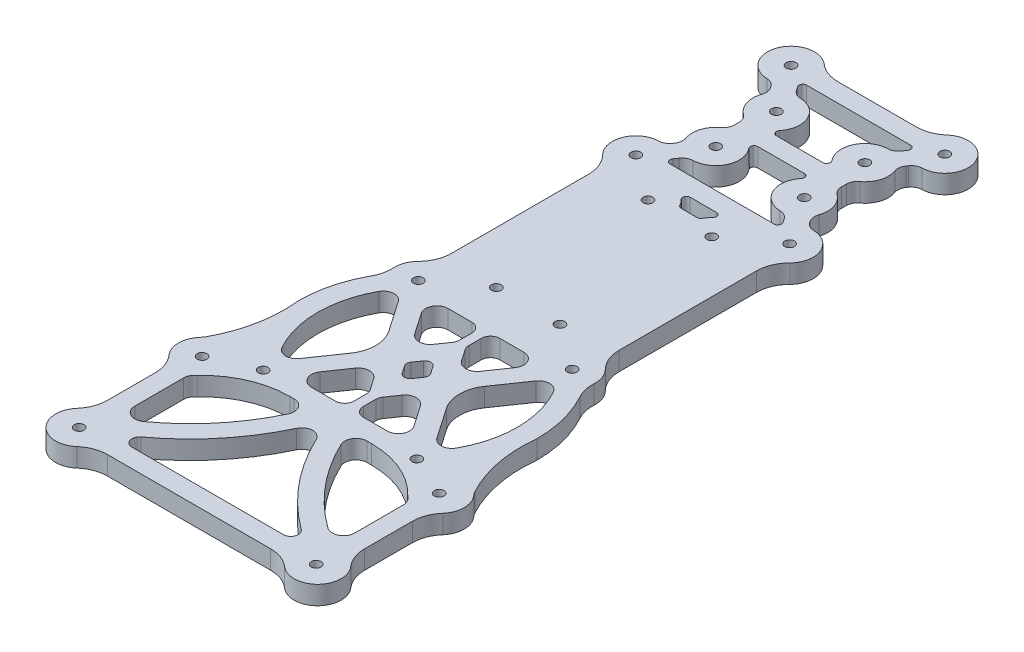
SolidWorks part; units mm, degrees
material "Acrylic (Medium-high impact)"
ref_plane "Front Plane" through (0, 0, 0) normal (0, 0, 1) x (1, 0, 0)
ref_plane "Top Plane" through (0, 0, 0) normal (0, 1, 0) x (1, 0, 0)
ref_plane "Right Plane" through (0, 0, 0) normal (1, 0, 0) x (0, 0, -1)
sketch "Sketch1" plane through (0, 0, 0) normal (0, 1, 0) x (1, 0, 0)
  line L0 (-37.2814, 102.0445) -> (37.2814, 102.0445) construction
  line L1 (-16.2987, -57.0117) -> (-23.4407, -46.6537)
  line L2 (-28.575, -23.3842) -> (-28.575, 23.3842)
  line L3 (-28.575, 39.1353) -> (28.575, 39.1353) construction
  line L4 (28.575, -23.3842) -> (28.575, 23.3842)
  line L5 (-28.575, -39.1353) -> (28.575, 39.1353) construction
  line L6 (-28.575, 39.1353) -> (28.575, -39.1353) construction
  line L7 (-10.8458, -25.8445) -> (10.8458, -25.8445) construction
  line L8 (-10.8458, -25.8445) -> (-10.8458, 25.8445) construction
  line L9 (-10.8458, 25.8445) -> (10.8458, 25.8445) construction
  line L10 (10.8458, -25.8445) -> (10.8458, 25.8445) construction
  line L11 (-10.8458, -25.8445) -> (10.8458, 25.8445) construction
  line L12 (-10.8458, 25.8445) -> (10.8458, -25.8445) construction
  line L13 (-87.957, -127.4445) -> (87.957, -127.4445) construction
  line L14 (0, -142.7251) -> (0, -89.9414) construction
  line L15 (-18.7815, 84.7755) -> (-17.8802, 83.4683)
  line L16 (-15.0876, 53.1749) -> (15.0876, 53.1749) construction
  line L17 (-15.0876, 53.1749) -> (-15.0876, 73.8251) construction
  line L18 (-15.0876, 73.8251) -> (15.0876, 73.8251) construction
  line L19 (15.0876, 53.1749) -> (15.0876, 73.8251) construction
  line L20 (-15.0876, 53.1749) -> (15.0876, 73.8251) construction
  line L21 (-15.0876, 73.8251) -> (15.0876, 53.1749) construction
  line L22 (-26.2001, 37.0586) -> (26.2001, 37.0586) construction
  line L23 (-26.2001, 37.0586) -> (-26.2001, 89.9414) construction
  line L24 (-26.2001, 89.9414) -> (26.2001, 89.9414) construction
  line L25 (26.2001, 37.0586) -> (26.2001, 89.9414) construction
  line L26 (-26.2001, 37.0586) -> (26.2001, 89.9414) construction
  line L27 (-26.2001, 89.9414) -> (26.2001, 37.0586) construction
  line L28 (18.7815, 84.7755) -> (17.8802, 83.4683)
  line L29 (-17.736, 86.7664) -> (17.736, 86.7664)
  line L30 (-26.2001, 86.7664) -> (26.2001, 86.7664) construction
  line L31 (-26.2001, 89.9414) -> (-15.0876, 73.8251) construction
  line L32 (-7.9199, 60.325) -> (7.9199, 60.325)
  line L33 (23.4075, 80.2982) -> (23.1079, 79.8637)
  line L34 (-18.2626, 53.1749) -> (-18.2626, 73.8251) construction
  line L35 (-15.0876, 53.1749) -> (-26.2001, 37.0586) construction
  line L36 (-13.3838, 93.1164) -> (13.3838, 93.1164)
  line L37 (-23.1079, 47.1363) -> (-23.4075, 46.7018)
  line L38 (-17.8802, 43.5317) -> (-18.7815, 42.2245)
  line L39 (-17.7015, 54.9772) -> (-28.814, 38.8609) construction
  line L40 (-12.4737, 51.3726) -> (-23.5862, 35.2563) construction
  line L41 (-18.2626, 62.6991) -> (-18.2626, 64.3009)
  line L42 (-11.9126, 60.325) -> (11.9126, 60.325) construction
  line L43 (17.8802, 43.5317) -> (18.7815, 42.2245)
  line L44 (-11.9126, 63.5) -> (11.9126, 63.5) construction
  line L45 (-17.736, 40.2336) -> (17.736, 40.2336)
  line L46 (-26.2001, 93.1164) -> (26.2001, 93.1164) construction
  line L47 (23.1079, 47.1363) -> (23.4075, 46.7018)
  line L48 (-23.5862, 91.7437) -> (-22.3435, 89.9414)
  line L49 (-23.5862, 91.7437) -> (-12.4737, 75.6274) construction
  line L50 (-23.4075, 80.2982) -> (-23.1079, 79.8637)
  line L51 (18.2626, 62.6991) -> (18.2626, 64.3009)
  line L52 (0, 0) -> (-28.575, 0) construction
  line L53 (-4.4705, 33.8455) -> (4.4705, 33.8455)
  line L54 (-2.7099, 29.0195) -> (2.7099, 29.0195)
  line L55 (-26.2001, 33.8455) -> (26.2001, 33.8455) construction
  line L56 (-10.8458, 29.0195) -> (10.8458, 29.0195) construction
  line L57 (-7.9199, 66.675) -> (7.9199, 66.675)
  line L58 (-11.9126, 66.675) -> (11.9126, 66.675) construction
  line L59 (-26.2001, -37.0586) -> (26.2001, -37.0586) construction
  line L60 (26.2001, -37.0586) -> (26.2001, -89.9414) construction
  line L61 (-26.2001, -37.0586) -> (-26.2001, -89.9414) construction
  line L62 (-26.2001, -89.9414) -> (26.2001, -89.9414) construction
  line L63 (-11.1049, -53.3578) -> (-16.0359, -46.2064)
  line L64 (-3.3465, -62.3903) -> (-1.6094, -59.8711)
  line L65 (1.5875, -43.4148) -> (1.5875, -47.6625)
  line L66 (-1.6094, -67.1289) -> (-3.3465, -64.6097)
  line L67 (-1.5875, -83.5852) -> (-1.5875, -79.3375)
  line L68 (-11.8248, -63.5) -> (-40.6867, -63.5) construction
  line L69 (4.7687, -40.2336) -> (12.8993, -40.2336)
  line L70 (2.1497, -49.4683) -> (4.8316, -53.3578)
  line L71 (-12.8993, -86.7664) -> (-4.7687, -86.7664)
  line L72 (-26.2001, -86.7664) -> (26.2001, -86.7664) construction
  line L73 (-13.9062, -93.1486) -> (-12.4524, -93.1486)
  line L74 (11.8248, -63.5) -> (40.6867, -63.5) construction
  line L75 (16.0359, -80.7936) -> (11.1049, -73.6422)
  line L76 (23.4407, -80.3463) -> (16.2987, -69.9883)
  line L77 (2.1497, -77.5317) -> (4.8316, -73.6422)
  line L78 (1.6094, -67.1289) -> (3.3465, -64.6097)
  line L79 (-23.4407, -80.3463) -> (-16.2987, -69.9883)
  line L80 (-16.0359, -80.7936) -> (-11.1049, -73.6422)
  line L81 (-1.5875, -43.4148) -> (-1.5875, -47.6625)
  line L82 (3.3465, -62.3903) -> (1.6094, -59.8711)
  line L83 (11.1049, -53.3578) -> (16.0359, -46.2064)
  line L84 (16.2987, -57.0117) -> (23.4407, -46.6537)
  line L85 (0, -67.9741) -> (0, 102.0445) construction
  line L86 (-40.6373, -138.2014) -> (40.3379, -138.2014) construction
  line L87 (-40.6373, -138.2014) -> (-40.6373, -96.2914) construction
  line L88 (-40.6373, -96.2914) -> (40.3379, -96.2914) construction
  line L89 (40.3379, -138.2014) -> (40.3379, -96.2914) construction
  line L90 (43.8123, -125.3851) -> (43.8123, -109.1077)
  line L91 (-40.6373, -96.2914) -> (40.3379, -138.2014) construction
  line L92 (0, -86.7664) -> (0, -79.1605) construction
  line L93 (1.5875, -83.5852) -> (1.5875, -79.3375)
  line L94 (-1.5875, -78.3471) -> (-1.5875, -78.3464)
  line L95 (-1.5875, -86.7664) -> (-1.5875, -79.1605) construction
  line L96 (1.5875, -86.7664) -> (1.5875, -79.1605) construction
  line L97 (4.7687, -86.7664) -> (12.8993, -86.7664)
  line L98 (-2.1497, -77.5317) -> (-4.8316, -73.6422)
  line L99 (-12.8993, -40.2336) -> (-4.7687, -40.2336)
  line L100 (-2.1497, -49.4683) -> (-4.8316, -53.3578)
  line L101 (-37.4623, -122.4001) -> (-37.4623, -105.8156)
  line L102 (-43.8123, -125.3851) -> (-43.8123, -109.1077)
  line L103 (-43.8123, -138.2014) -> (-43.8123, -96.2914) construction
  line L104 (-37.4623, -138.2014) -> (-37.4623, -96.2914) construction
  line L105 (-27.821, -141.3764) -> (27.821, -141.3764)
  line L106 (-25.7796, -135.0264) -> (25.7796, -135.0264)
  line L107 (-40.6373, -141.3764) -> (40.3379, -141.3764) construction
  line L108 (-40.6373, -135.0264) -> (40.3379, -135.0264) construction
  line L109 (-40.6373, -138.2014) -> (40.3379, -96.2914) construction
  line L110 (37.4623, -122.4001) -> (37.4623, -105.8156)
  line L111 (13.9062, -93.1486) -> (12.4524, -93.1486)
  circle A0 centre (-10.8458, 25.8445) radius 1.651
  circle A1 centre (10.8458, 25.8445) radius 1.651
  circle A2 centre (-10.8458, -25.8445) radius 1.651
  circle A3 centre (10.8458, -25.8445) radius 1.651
  circle A4 centre (-15.0876, 73.8251) radius 1.651
  circle A5 centre (15.0876, 73.8251) radius 1.651
  circle A6 centre (-15.0876, 53.1749) radius 1.651
  circle A7 centre (15.0876, 53.1749) radius 1.651
  circle A8 centre (-26.2001, 89.9414) radius 1.651
  circle A9 centre (26.2001, 89.9414) radius 1.651
  circle A10 centre (26.2001, 37.0586) radius 1.651
  circle A11 centre (-26.2001, 37.0586) radius 1.651
  arc A12 (-20.9228, 95.9552) -> (-26.4332, 81.9438) centre (-26.2001, 89.9414) ccw
  arc A13 (-22.6455, 76.4507) -> (-19.8194, 67.3733) centre (-15.0876, 73.8251) ccw
  circle A14 centre (-15.0876, 73.8251) radius 8.001 construction
  circle A15 centre (-26.2001, 89.9414) radius 8.001 construction
  arc A16 (-23.4075, 80.2982) -> (-26.4332, 81.9438) centre (-26.5442, 78.1354) ccw
  arc A17 (22.6455, 76.4507) -> (19.8194, 67.3733) centre (15.0876, 73.8251) cw
  arc A18 (-22.6455, 50.5493) -> (-19.8194, 59.6267) centre (-15.0876, 53.1749) cw
  arc A19 (14.8545, 81.8227) -> (17.8802, 83.4683) centre (14.7435, 85.6311) ccw
  arc A20 (-18.7815, 42.2245) -> (-17.736, 40.2336) centre (-17.736, 41.5036) ccw
  arc A21 (-31.8845, 31.428) -> (-26.4332, 45.0562) centre (-26.2001, 37.0586) cw
  arc A22 (17.736, 86.7664) -> (18.7815, 84.7755) centre (17.736, 85.4964) cw
  arc A23 (-17.8802, 43.5317) -> (-14.8545, 45.1773) centre (-14.7435, 41.3689) cw
  arc A24 (31.8845, 31.428) -> (26.4332, 45.0562) centre (26.2001, 37.0586) ccw
  arc A25 (28.575, 23.3842) -> (31.8845, 31.428) centre (40.005, 23.3842) cw
  arc A26 (-8.9018, 58.2495) -> (-14.8545, 45.1773) centre (-15.0876, 53.1749) cw
  arc A27 (-22.6455, 76.4507) -> (-23.1079, 79.8637) centre (-26.2446, 77.7009) ccw
  arc A28 (22.6455, 76.4507) -> (23.1079, 79.8637) centre (26.2446, 77.7009) cw
  arc A29 (23.4075, 80.2982) -> (26.4332, 81.9438) centre (26.5442, 78.1354) cw
  arc A30 (20.9228, 95.9552) -> (26.4332, 81.9438) centre (26.2001, 89.9414) cw
  arc A31 (-31.8845, 31.428) -> (-28.575, 23.3842) centre (-40.005, 23.3842) cw
  arc A32 (13.3838, 93.1164) -> (20.9228, 95.9552) centre (13.3838, 104.5464) ccw
  arc A33 (-13.3838, 93.1164) -> (-20.9228, 95.9552) centre (-13.3838, 104.5464) cw
  arc A34 (-14.8545, 81.8227) -> (-17.8802, 83.4683) centre (-14.7435, 85.6311) cw
  arc A35 (-17.736, 86.7664) -> (-18.7815, 84.7755) centre (-17.736, 85.4964) ccw
  arc A36 (-8.9018, 68.7505) -> (-14.8545, 81.8227) centre (-15.0876, 73.8251) ccw
  arc A37 (-26.4332, 45.0562) -> (-23.4075, 46.7018) centre (-26.5442, 48.8646) ccw
  arc A38 (-23.1079, 47.1363) -> (-22.6455, 50.5493) centre (-26.2446, 49.2991) ccw
  arc A39 (-19.8194, 67.3733) -> (-18.2626, 64.3009) centre (-22.0726, 64.3009) cw
  arc A40 (-19.8194, 59.6267) -> (-18.2626, 62.6991) centre (-22.0726, 62.6991) ccw
  arc A41 (-8.9018, 58.2495) -> (-7.9199, 60.325) centre (-7.9199, 59.055) cw
  arc A42 (-8.9018, 68.7505) -> (-7.9199, 66.675) centre (-7.9199, 67.945) ccw
  arc A43 (18.7815, 42.2245) -> (17.736, 40.2336) centre (17.736, 41.5036) cw
  arc A44 (17.8802, 43.5317) -> (14.8545, 45.1773) centre (14.7435, 41.3689) ccw
  arc A45 (26.4332, 45.0562) -> (23.4075, 46.7018) centre (26.5442, 48.8646) cw
  arc A46 (23.1079, 47.1363) -> (22.6455, 50.5493) centre (26.2446, 49.2991) cw
  arc A47 (22.6455, 50.5493) -> (19.8194, 59.6267) centre (15.0876, 53.1749) ccw
  arc A48 (8.9018, 58.2495) -> (14.8545, 45.1773) centre (15.0876, 53.1749) ccw
  arc A49 (8.9018, 58.2495) -> (7.9199, 60.325) centre (7.9199, 59.055) ccw
  arc A50 (19.8194, 59.6267) -> (18.2626, 62.6991) centre (22.0726, 62.6991) cw
  arc A51 (19.8194, 67.3733) -> (18.2626, 64.3009) centre (22.0726, 64.3009) ccw
  arc A52 (8.9018, 68.7505) -> (7.9199, 66.675) centre (7.9199, 67.945) cw
  arc A53 (8.9018, 68.7505) -> (14.8545, 81.8227) centre (15.0876, 73.8251) cw
  arc A54 (-3.8244, 29.6806) -> (-5.3438, 31.6534) centre (-10.8458, 25.8445) ccw
  arc A55 (-3.8244, 29.6806) -> (-2.7099, 29.0195) centre (-2.7099, 30.2895) ccw
  arc A56 (-4.4705, 33.8455) -> (-5.3438, 31.6534) centre (-4.4705, 32.5755) ccw
  circle A57 centre (-10.8458, 25.8445) radius 8.001 construction
  arc A58 (3.8244, 29.6806) -> (2.7099, 29.0195) centre (2.7099, 30.2895) cw
  arc A59 (3.8244, 29.6806) -> (5.3438, 31.6534) centre (10.8458, 25.8445) cw
  arc A60 (4.4705, 33.8455) -> (5.3438, 31.6534) centre (4.4705, 32.5755) cw
  arc A61 (-31.8845, -31.428) -> (-34.1873, -37.5281) centre (-26.2001, -37.0586) ccw
  arc A62 (-16.2987, -57.0117) -> (-16.2987, -69.9883) centre (-25.7086, -63.5) cw
  arc A63 (41.7138, -135.1363) -> (3.2569, -92.936) centre (72.2758, -68.6624) cw construction
  arc A64 (-23.4407, -80.3463) -> (-29.7178, -80.0342) centre (-26.4827, -78.2487) cw
  circle A65 centre (26.2001, -89.9414) radius 1.651
  circle A66 centre (-26.2001, -89.9414) radius 1.651
  circle A67 centre (-26.2001, -37.0586) radius 1.651
  circle A68 centre (26.2001, -37.0586) radius 1.651
  arc A69 (-23.4407, -46.6537) -> (-29.7178, -46.9658) centre (-26.4827, -48.7513) ccw
  arc A70 (-45.7315, -89.727) -> (-46.5906, -90.9459) centre (-51.3154, -86.7034) cw
  arc A71 (-35.5908, -43.7222) -> (-34.1873, -37.5281) centre (-45.5976, -38.1988) ccw
  arc A72 (-4.8316, -73.6422) -> (-11.1049, -73.6422) centre (-7.9682, -75.805) ccw
  arc A73 (-11.1049, -53.3578) -> (-4.8316, -53.3578) centre (-7.9682, -51.195) ccw
  arc A74 (-12.8993, -40.2336) -> (-16.0359, -46.2064) centre (-12.8993, -44.0436) ccw
  arc A75 (-16.0359, -80.7936) -> (-12.8993, -86.7664) centre (-12.8993, -82.9564) ccw
  arc A76 (35.9055, -102.7432) -> (13.9062, -93.1486) centre (13.9062, -123.1667) ccw
  arc A77 (-31.8845, -31.428) -> (-28.575, -23.3842) centre (-40.005, -23.3842) ccw
  arc A78 (31.2199, -43.289) -> (26.2001, -89.9414) centre (-0.2413, -63.5) cw construction
  arc A79 (29.7178, -46.9658) -> (29.7178, -80.0342) centre (-0.2413, -63.5) cw
  arc A80 (35.5908, -43.7222) -> (40.6867, -63.5) centre (-0.2413, -63.5) cw
  arc A81 (-35.5908, -43.7222) -> (-40.6867, -63.5) centre (0.2413, -63.5) ccw
  arc A82 (31.8845, -31.428) -> (28.575, -23.3842) centre (40.005, -23.3842) cw
  arc A83 (-29.7178, -46.9658) -> (-29.7178, -80.0342) centre (0.2413, -63.5) ccw
  arc A84 (25.7796, -135.0264) -> (27.28, -130.437) centre (25.7796, -132.4864) ccw
  arc A85 (-31.2199, -43.289) -> (-26.2001, -89.9414) centre (0.2413, -63.5) ccw construction
  arc A86 (16.0359, -80.7936) -> (12.8993, -86.7664) centre (12.8993, -82.9564) cw
  arc A87 (12.8993, -40.2336) -> (16.0359, -46.2064) centre (12.8993, -44.0436) cw
  arc A88 (11.1049, -53.3578) -> (4.8316, -53.3578) centre (7.9682, -51.195) cw
  arc A89 (4.8316, -73.6422) -> (11.1049, -73.6422) centre (7.9682, -75.805) cw
  arc A90 (35.5908, -43.7222) -> (34.1873, -37.5281) centre (45.5976, -38.1988) cw
  circle A91 centre (-40.6373, -138.2014) radius 8.001 construction
  arc A92 (23.4407, -46.6537) -> (29.7178, -46.9658) centre (26.4827, -48.7513) cw
  circle A93 centre (26.2001, -37.0586) radius 1.651
  circle A94 centre (26.2001, -89.9414) radius 1.651
  arc A95 (23.4407, -80.3463) -> (29.7178, -80.0342) centre (26.4827, -78.2487) ccw
  arc A96 (-43.8123, -125.3851) -> (-46.6511, -132.9241) centre (-55.2423, -125.3851) cw
  arc A97 (16.2987, -57.0117) -> (16.2987, -69.9883) centre (25.7086, -63.5) ccw
  arc A98 (31.8845, -31.428) -> (34.1873, -37.5281) centre (26.2001, -37.0586) cw
  arc A99 (1.6094, -67.1289) -> (-1.6094, -67.1289) centre (0, -66.0192) cw
  arc A100 (-3.3465, -64.6097) -> (-3.3465, -62.3903) centre (-1.737, -63.5) cw
  arc A101 (1.6094, -59.8711) -> (-1.6094, -59.8711) centre (0, -60.9808) ccw
  arc A102 (3.3465, -64.6097) -> (3.3465, -62.3903) centre (1.737, -63.5) ccw
  arc A103 (2.1497, -77.5317) -> (1.5875, -79.3375) centre (4.7687, -79.3375) ccw
  arc A104 (-2.1497, -49.4683) -> (-1.5875, -47.6625) centre (-4.7687, -47.6625) ccw
  circle A105 centre (-40.6373, -96.2914) radius 1.651
  circle A106 centre (40.1347, -96.2914) radius 1.651
  circle A107 centre (40.1347, -138.2014) radius 1.651
  circle A108 centre (-40.6373, -138.2014) radius 1.651
  arc A109 (-46.5906, -90.9459) -> (-46.6511, -101.5687) centre (-40.6373, -96.2914) ccw
  arc A110 (-46.6511, -132.9241) -> (-35.36, -144.2152) centre (-40.6373, -138.2014) ccw
  arc A111 (-43.8123, -109.1077) -> (-46.6511, -101.5687) centre (-55.2423, -109.1077) ccw
  arc A112 (-9.0082, -98.5876) -> (-12.4524, -93.1486) centre (-12.4524, -96.9586) ccw
  arc A113 (1.5875, -83.5852) -> (4.7687, -86.7664) centre (4.7687, -83.5852) ccw
  arc A114 (-1.5875, -83.5852) -> (-4.7687, -86.7664) centre (-4.7687, -83.5852) cw
  arc A115 (-2.1497, -77.5317) -> (-1.5875, -79.3375) centre (-4.7687, -79.3375) cw
  arc A116 (2.1497, -49.4683) -> (1.5875, -47.6625) centre (4.7687, -47.6625) cw
  arc A117 (1.5875, -43.4148) -> (4.7687, -40.2336) centre (4.7687, -43.4148) cw
  arc A118 (-1.5875, -43.4148) -> (-4.7687, -40.2336) centre (-4.7687, -43.4148) ccw
  arc A119 (-45.7315, -89.727) -> (-40.6867, -63.5) centre (-84.6823, -68.6361) ccw
  circle A120 centre (-40.6373, -96.2914) radius 8.001 construction
  arc A121 (-27.821, -141.3764) -> (-35.36, -144.2152) centre (-27.821, -152.8064) ccw
  arc A122 (-37.4623, -105.8156) -> (-35.9055, -102.7432) centre (-33.6523, -105.8156) cw
  arc A123 (-31.4286, -125.4939) -> (-9.0082, -98.5876) centre (-72.2758, -68.6624) ccw
  arc A124 (-41.7138, -135.1363) -> (-3.2569, -92.936) centre (-72.2758, -68.6624) ccw construction
  arc A125 (-27.28, -130.437) -> (-3.3205, -101.3825) centre (-72.3759, -68.8428) ccw
  arc A126 (-43.0401, -132.2516) -> (-5.9203, -90.9169) centre (-72.2758, -68.6624) ccw construction
  arc A127 (-41.7138, -135.1363) -> (-2.9101, -91.9264) centre (-72.2758, -68.6624) ccw construction
  arc A128 (-31.4286, -125.4939) -> (-37.4623, -122.4001) centre (-33.6523, -122.4001) cw
  arc A129 (-25.7796, -135.0264) -> (-27.28, -130.437) centre (-25.7796, -132.4864) cw
  arc A130 (31.4286, -125.4939) -> (37.4623, -122.4001) centre (33.6523, -122.4001) ccw
  arc A131 (-35.9055, -102.7432) -> (-13.9062, -93.1486) centre (-13.9062, -123.1667) cw
  arc A132 (27.28, -130.437) -> (3.3205, -101.3825) centre (72.3759, -68.8428) cw
  arc A133 (31.4286, -125.4939) -> (9.0082, -98.5876) centre (72.2758, -68.6624) cw
  arc A134 (37.4623, -105.8156) -> (35.9055, -102.7432) centre (33.6523, -105.8156) ccw
  arc A135 (27.821, -141.3764) -> (35.36, -144.2152) centre (27.821, -152.8064) cw
  arc A136 (45.7315, -89.727) -> (40.6867, -63.5) centre (84.6823, -68.6361) cw
  arc A137 (9.0082, -98.5876) -> (12.4524, -93.1486) centre (12.4524, -96.9586) cw
  arc A138 (43.8123, -109.1077) -> (46.6511, -101.5687) centre (55.2423, -109.1077) cw
  arc A139 (46.6511, -132.9241) -> (35.36, -144.2152) centre (40.6373, -138.2014) cw
  arc A140 (46.5906, -90.9459) -> (46.6511, -101.5687) centre (40.6373, -96.2914) cw
  arc A141 (43.8123, -125.3851) -> (46.6511, -132.9241) centre (55.2423, -125.3851) ccw
  arc A142 (45.7315, -89.727) -> (46.5906, -90.9459) centre (51.3154, -86.7034) ccw
  arc A143 (3.3205, -101.3825) -> (-3.3205, -101.3825) centre (0, -102.9471) ccw
  point P0 (0, 0)
  point P6 (0, 0)
  point P22 (0, -127.4445)
  point P24 (0, 102.0445)
  point P26 (0, 63.5)
  point P32 (0, 63.5)
  point P60 (0, 97.9424)
  point P74 (0, 86.7664)
  point P96 (-21.6745, 69.2833)
  point P121 (-20.1543, 86.7664)
  point P126 (-21.8704, 48.9311)
  point P135 (-11.9126, 66.481)
  point P140 (0, 40.2336)
  point P160 (0, 60.325)
  point P175 (0, 29.0195)
  point P180 (0, 33.8455)
  point P186 (0, 66.675)
  point P191 (0, -40.2336)
  point P193 (0, -86.7664)
  point P233 (-7.9682, -57.9068)
  point P288 (0, -93.1164)
  point P289 (7.9682, -57.9068)
  point P292 (0, -69.4631)
  point P295 (-4.1116, -63.5)
  point P298 (0, -57.5369)
  point P301 (4.1116, -63.5)
  point P304 (0, -80.6494)
  point P307 (0, -46.3506)
  point P308 (0, -117.3239)
  point P359 (-46.1627, -90.5047)
  point P364 (0, -141.3764)
  point P365 (37.4623, -103.6355)
  point P383 (-37.4623, -103.6355)
  point P419 (0, -135.0264)
  point P420 (46.1627, -90.5047)
  dimension "D3" = 3.302
  dimension "D11" = 3.302
  dimension "D16" = 3.302
  dimension "D23" = 3.81
  dimension "D24" = 3.175
  dimension "D25" = 11.43
  dimension "D27" = 3.175
  dimension "D28" = 1.27
  dimension "D31" = 1.27
  dimension "D32" = 3.81
  dimension "D33" = 1.27
  dimension "D38" = 1.27
  dimension "D7" = 11.43
  dimension "D40" = 3.81
  dimension "D42" = 3.81
  dimension "D44" = 1.9549
  dimension "D48" = 3.302
  dimension "D54" = 3.1812
  dimension "D39" = 6.35
  dimension "D56" = 11.43
  dimension "D59" = 11.43
  dimension "D60" = 3.81
  dimension "D62" = 2.54
  dimension "D1" = 21.6916
  dimension "D2" = 51.689
  dimension "D6" = 76.2
  dimension "D8" = 101.6
  dimension "D9" = 30.1752
  dimension "D10" = 20.6502
  dimension "D14" = 52.8828
  dimension "D15" = 52.4002
  dimension "D19" = 63.5
  dimension "D45" = 41.91
  dimension "D46" = 80.9752
  dimension "D47" = 6.35
  dimension "D20" = 6.35
  dimension "D21" = 6.35
  dimension "D22" = 3.175
  dimension "D26" = 3.175
  dimension "D29" = 3.175
  dimension "D30" = 3.175
  dimension "D34" = 6.35
  dimension "D35" = 3.175
  dimension "D36" = 3.175
  dimension "D37" = 3.175
  dimension "D41" = 3.175
  dimension "D51" = 6.35
  dimension "D52" = 1.5875
  dimension "D53" = 1.5875
  dimension "D55" = 3.175
  dimension "D57" = 3.175
  dimension "D58" = 3.175
  dimension "D61" = 3.175
  dimension "D4" = 2
  dimension "D5" = 2
  dimension "D12" = 2
  dimension "D13" = 2
  dimension "D17" = 2
  dimension "D18" = 2
  dimension "D49" = 2
  dimension "D50" = 2
extrude "Boss-Extrude1" add sketch "Sketch1" against normal blind 6.35
